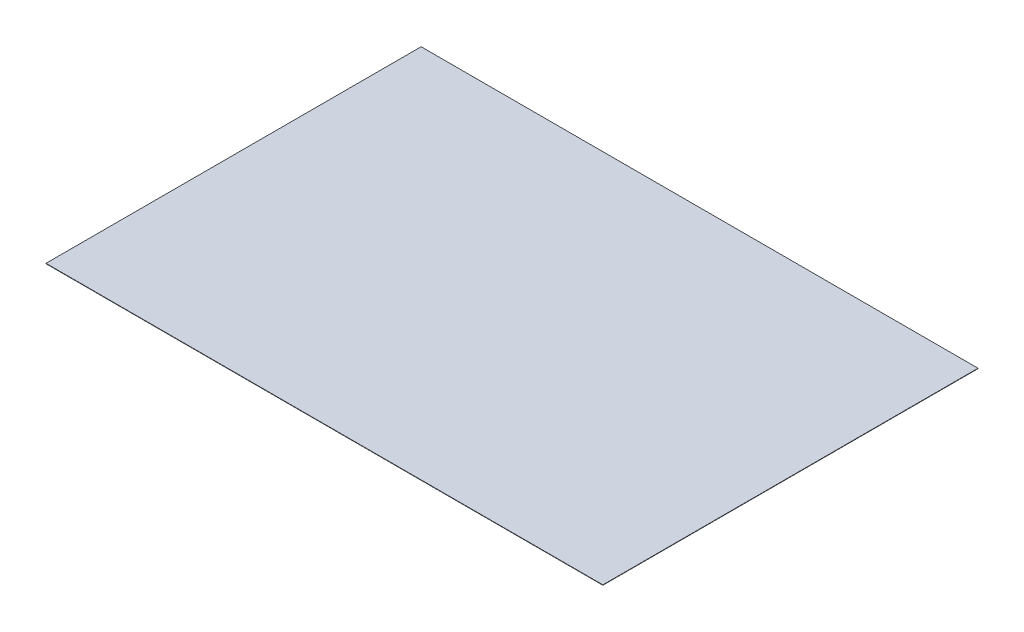
SolidWorks part; units mm, degrees
ref_plane "前视基准面" through (0, 0, 0) normal (0, 0, 1) x (1, 0, 0)
ref_plane "上视基准面" through (0, 0, 0) normal (0, 1, 0) x (1, 0, 0)
ref_plane "右视基准面" through (0, 0, 0) normal (1, 0, 0) x (0, 0, -1)
other "Configuration Table"
sketch "草图1" plane through (0, 0, 0) normal (0, 1, 0) x (1, 0, 0)
  line L1 (-74, -49.85) -> (74, -49.85)
  line L2 (-74, -49.85) -> (-74, 49.85)
  line L3 (-74, 49.85) -> (74, 49.85)
  line L4 (74, -49.85) -> (74, 49.85)
  line L5 (-74, -49.85) -> (74, 49.85) construction
  line L6 (-74, 49.85) -> (74, -49.85) construction
  dimension "D1" = 99.7
  dimension "D2" = 148
extrude "凸台-拉伸1" add sketch "草图1" along normal blind 0.1
